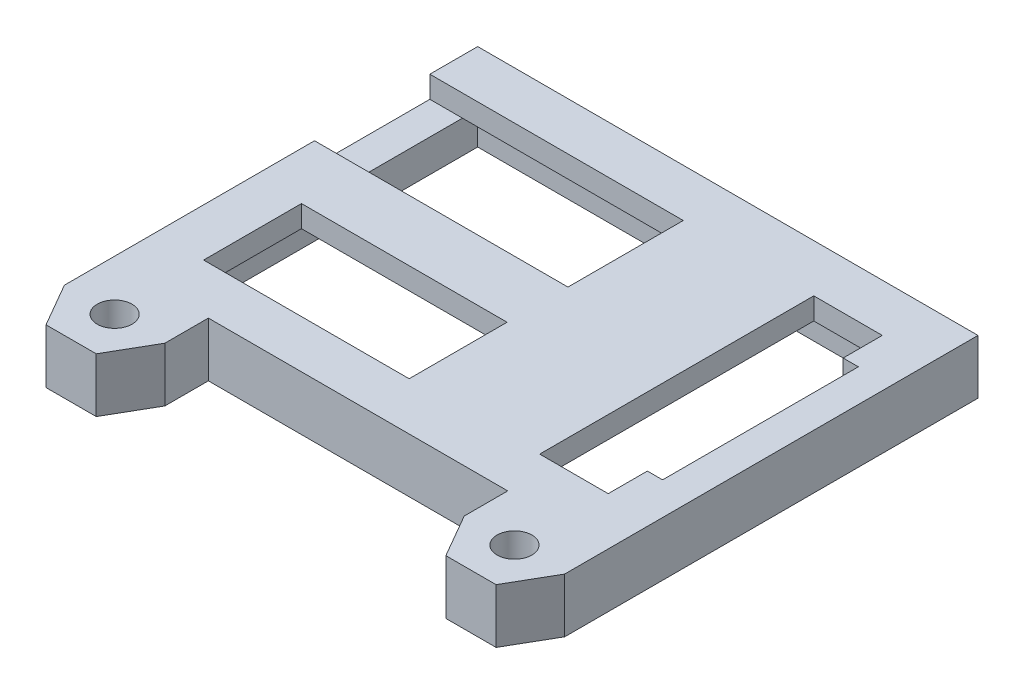
SolidWorks part; units mm, degrees
ref_plane "Alzado" through (0, 0, 0) normal (0, 0, 1) x (1, 0, 0)
ref_plane "Planta" through (0, 0, 0) normal (0, 1, 0) x (1, 0, 0)
ref_plane "Vista lateral" through (0, 0, 0) normal (1, 0, 0) x (0, 0, -1)
sketch "Croquis1" plane through (0, 0, 0) normal (0, 1, 0) x (1, 0, 0)
  line L0 (0, -1000) -> (0, 49000) construction
  line L1 (-20, 14) -> (20, 14) construction
  line L2 (-20, 14) -> (-20, -14) construction
  line L3 (-20, -14) -> (20, -14) construction
  line L4 (20, 14) -> (20, -14) construction
  line L5 (-20, 14) -> (20, -14) construction
  line L6 (-20, -14) -> (20, 14) construction
  line L7 (-23, 17) -> (23, 17)
  line L8 (23, 17) -> (23, -17)
  line L9 (-23, -17) -> (23, -17)
  line L10 (-23, 17) -> (-23, -17)
  line L11 (-18.6, 12.6) -> (18.6, 12.6)
  line L12 (18.6, 12.6) -> (18.6, 9)
  line L13 (-18.6, -12.6) -> (18.6, -12.6)
  line L14 (-18.6, 12.6) -> (-18.6, -12.6)
  line L15 (-1000, 0) -> (49000, 0) construction
  line L16 (13.5, -9) -> (20, -9)
  line L17 (13.5, -9) -> (13.5, 9)
  line L18 (20, -9) -> (20, 9)
  line L19 (13.5, 9) -> (20, 9)
  line L20 (13.5, -9) -> (20, 9) construction
  line L21 (20, -9) -> (13.5, 9) construction
  line L22 (18.6, -9) -> (18.6, -12.6)
  line L23 (18.6, 12.6) -> (18.6, -12.6) construction
  line L24 (0.3, 12.6) -> (0.3, -12.6)
  line L25 (12.3, -12.6) -> (12.3, 12.6)
  line L26 (-18.6, 2) -> (0.3, 2)
  line L27 (-18.6, -3.6) -> (0.3, -3.6)
  line L28 (-18.6, 2) -> (-23, 2)
  line L29 (-18.6, 12.6) -> (-23, 12.6)
  point P0 (0, 0)
  point P19 (16.75, 0)
  dimension "D1" = 40
  dimension "D2" = 28
  dimension "D5" = 18
  dimension "D6" = 6.5
  dimension "D7" = 12
  dimension "D8" = 1.2
  dimension "D9" = 12
  dimension "D10" = 9
  dimension "D3" = 3
  dimension "D4" = 1.4
extrude "Saliente-Extruir1" add sketch "Croquis1" against normal blind 2 contours L7 L10 L9 L8 L16 L22 L13 L14 L11 L12 L19 L18 | L13 L25 L11 L24 | L14 L27 L24 L26
sketch "Croquis2" plane through (0, -2, 0) normal (0, -1, 0) x (1, 0, 0)
  line L0 (-23, -17) -> (-23, 17) construction
  line L1 (-23, 17) -> (23, 17) construction
  line L2 (23, -17) -> (23, 17) construction
  line L3 (-23, -17) -> (23, -17) construction
  line L4 (-20, -14) -> (20, -14) construction
  line L8 (20, -14) -> (20, 14) construction
  line L9 (-20, 14) -> (20, 14) construction
  line L10 (-20, -14) -> (-20, 14) construction
  line L11 (-23, -17) -> (-23, -12.6)
  line L12 (-23, 17) -> (23, 17)
  line L13 (23, -17) -> (23, 17)
  line L14 (-23, -17) -> (23, -17)
  line L15 (-20, -14) -> (20, -14)
  line L19 (20, -14) -> (20, 14)
  line L20 (-20, 14) -> (20, 14)
  line L21 (-20, -14) -> (-20, -12.6)
  line L23 (-23, -2) -> (-23, 17)
  line L24 (-20, -2) -> (-20, 14)
  line L25 (-23, -2) -> (-23, -12.6)
  line L26 (-20, -12.6) -> (-20, -2)
extrude "Saliente-Extruir2" add sketch "Croquis2" along normal blind 3
sketch "Croquis3" plane through (0, 0, 0) normal (0, 1, 0) x (1, 0, 0)
  line L0 (23, -17) -> (-23, -17) construction
  line L1 (-16.0718, -17) -> (-20.6906, -17)
  line L2 (-20.6906, -17) -> (-23, -21)
  line L3 (-23, -21) -> (-20.6906, -25)
  line L4 (-20.6906, -25) -> (-16.0718, -25)
  line L5 (-16.0718, -25) -> (-13.7624, -21)
  line L6 (-13.7624, -21) -> (-16.0718, -17)
  line L7 (0, -1000) -> (0, 49000) construction
  line L8 (13.7624, -21) -> (16.0718, -17)
  line L9 (20.6906, -25) -> (16.0718, -25)
  line L10 (23, -21) -> (20.6906, -25)
  line L11 (20.6906, -17) -> (23, -21)
  line L12 (16.0718, -17) -> (20.6906, -17)
  line L13 (16.0718, -25) -> (13.7624, -21)
  line L14 (-23, -17) -> (-23, -21)
  line L15 (23, -17) -> (23, -21)
  line L17 (-23, -17) -> (-20.6906, -17)
  line L18 (-16.0718, -17) -> (-13.7624, -17)
  line L19 (20.6906, -17) -> (23, -17)
  line L21 (-13.7624, -21) -> (-13.7624, -17)
  line L22 (13.7624, -21) -> (13.7624, -17)
  line L23 (13.7624, -17) -> (16.0718, -17)
  circle A0 centre (-18.3812, -21) radius 4 construction
  circle A1 centre (-18.3812, -21) radius 1.6
  circle A2 centre (18.3812, -21) radius 1.6
  point P23 (-17.2032, -22.0201)
  dimension "D1" = 3.2
  dimension "D2" = 8
extrude "Saliente-Extruir4" add sketch "Croquis3" against normal through all contours L5 L6 L1 L2 L3 L4 A1 | L13 L9 L10 L11 L12 L8 A2 | L17 L14 L2 | L6 L21 L18 | L23 L22 L8 | L19 L11 L15
